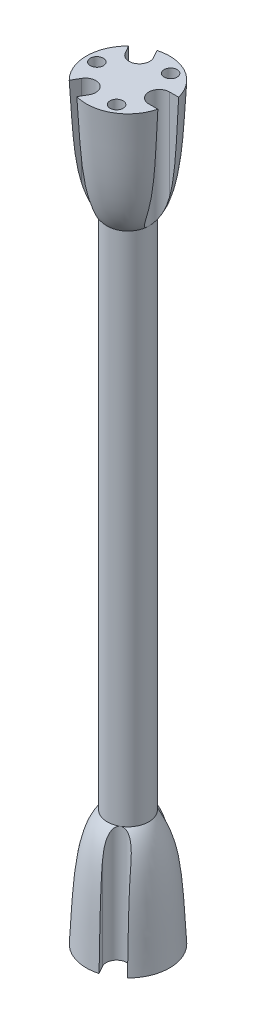
SolidWorks part; units mm, degrees
ref_plane "Front Plane" through (0, 0, 0) normal (0, 0, 1) x (1, 0, 0)
ref_plane "Top Plane" through (0, 0, 0) normal (0, 1, 0) x (1, 0, 0)
ref_plane "Right Plane" through (0, 0, 0) normal (1, 0, 0) x (0, 0, -1)
sketch "Sketch1" plane through (0, 0, 0) normal (0, 0, 1) x (1, 0, 0)
  line L0 (0, 0) -> (0, 38.1)
  line L1 (0, 0) -> (12.7, 0)
  line L9 (0, 228.6) -> (12.7, 228.6)
  line L10 (0, 228.6) -> (0, 190.5)
  spline S0 degree 3 poles (0, 38.1) (12.0762, 38.4029) (11.5808, 18.1012) (12.7, 0) knots 0 0 0 0 1 1 1 1
  spline S1 degree 3 poles (0, 190.5) (12.0762, 190.1971) (11.5808, 210.4988) (12.7, 228.6) knots 0 0 0 0 1 1 1 1
  point P8 (-152.1908, 114.3)
  dimension "D1" = 12.7
  dimension "D2" = 38.1
revolve "Revolve1" add sketch "Sketch1" angle 360 about L0
sketch "Sketch2" plane through (0, 0, 0) normal (0, -1, 0) x (1, 0, 0)
  circle A0 centre (0, 0) radius 6.35
  dimension "D1" = 12.7
extrude "Boss-Extrude1" add sketch "Sketch2" against normal blind 228.6
sketch "Sketch3" plane through (0, 0, 0) normal (0, -1, 0) x (-1, 0, 0)
  circle A0 centre (-9.525, 0) radius 2
  circle A1 centre (4.7625, 8.2489) radius 2
  circle A2 centre (4.7625, -8.2489) radius 2
  point P9 (0, 0)
  dimension "D1" = 4
  dimension "D2" = 9.525
  dimension "D3" = 3
extrude "Cut-Extrude1" cut sketch "Sketch3" against normal blind 7
sketch "Sketch4" plane through (0, 0, 0) normal (0, -1, 0) x (1, 0, 0)
  line L0 (7.9375, 13.7482) -> (4.7625, 8.2489) construction
  line L1 (-15.875, 0) -> (-9.525, 0) construction
  line L2 (-15.875, 3.175) -> (-9.525, 3.175)
  line L3 (-15.875, -3.175) -> (-9.525, -3.175)
  line L4 (10.6871, 12.1607) -> (7.5121, 6.6614)
  line L5 (5.1879, 15.3357) -> (2.0129, 9.8364)
  line L6 (7.9375, -13.7482) -> (4.7625, -8.2489) construction
  line L7 (5.1879, -15.3357) -> (2.0129, -9.8364)
  line L8 (10.6871, -12.1607) -> (7.5121, -6.6614)
  circle A1 centre (0, 0) radius 12.7 construction
  arc A2 (-15.875, 3.175) -> (-15.875, -3.175) centre (-15.875, 0) ccw
  arc A3 (-9.525, -3.175) -> (-9.525, 3.175) centre (-9.525, 0) ccw
  arc A4 (10.6871, 12.1607) -> (5.1879, 15.3357) centre (7.9375, 13.7482) ccw
  arc A5 (2.0129, 9.8364) -> (7.5121, 6.6614) centre (4.7625, 8.2489) ccw
  arc A6 (5.1879, -15.3357) -> (10.6871, -12.1607) centre (7.9375, -13.7482) ccw
  arc A7 (7.5121, -6.6614) -> (2.0129, -9.8364) centre (4.7625, -8.2489) ccw
  point P2 (0, 0)
  point P3 (0, 0)
  point P6 (-12.7, 0)
  point P14 (6.35, 10.9985)
  point P21 (6.35, -10.9985)
  point P26 (0, 0)
  point P27 (0, 0)
  point P28 (0, 0)
  point P29 (-9.525, -3.0626)
  dimension "D1" = 3
  dimension "D3" = 3.175
  dimension "D2" = 9.525
extrude "Cut-Extrude3" cut sketch "Sketch4" against normal up to next
sketch "Sketch5" plane through (0, 228.6, 0) normal (0, 1, 0) x (1, 0, 0)
  circle A0 centre (-9.525, 0) radius 2
  circle A1 centre (4.7625, 8.2489) radius 2
  circle A2 centre (4.7625, -8.2489) radius 2
  point P9 (0, 0)
  dimension "D1" = 4
  dimension "D2" = 9.525
  dimension "D3" = 3
extrude "Cut-Extrude4" cut sketch "Sketch5" against normal blind 7
sketch "Sketch6" plane through (0, 228.6, 0) normal (0, 1, 0) x (1, 0, 0)
  line L0 (15.875, 0) -> (9.525, 0) construction
  line L3 (15.875, -3.175) -> (9.525, -3.175)
  line L4 (15.875, 3.175) -> (9.525, 3.175)
  line L5 (-7.9375, -13.7482) -> (-4.7625, -8.2489) construction
  line L6 (-10.6871, -12.1607) -> (-7.5121, -6.6614)
  line L7 (-5.1879, -15.3357) -> (-2.0129, -9.8364)
  line L8 (-7.9375, 13.7482) -> (-4.7625, 8.2489) construction
  line L9 (-5.1879, 15.3357) -> (-2.0129, 9.8364)
  line L10 (-10.6871, 12.1607) -> (-7.5121, 6.6614)
  circle A4 centre (0, 0) radius 12.7 construction
  arc A5 (15.875, -3.175) -> (15.875, 3.175) centre (15.875, 0) ccw
  arc A6 (9.525, 3.175) -> (9.525, -3.175) centre (9.525, 0) ccw
  arc A7 (-10.6871, -12.1607) -> (-5.1879, -15.3357) centre (-7.9375, -13.7482) ccw
  arc A8 (-2.0129, -9.8364) -> (-7.5121, -6.6614) centre (-4.7625, -8.2489) ccw
  arc A9 (-5.1879, 15.3357) -> (-10.6871, 12.1607) centre (-7.9375, 13.7482) ccw
  arc A10 (-7.5121, 6.6614) -> (-2.0129, 9.8364) centre (-4.7625, 8.2489) ccw
  point P4 (12.7, 0)
  point P14 (-6.35, -10.9985)
  point P21 (-6.35, 10.9985)
  point P26 (0, 0)
  dimension "D1" = 3
  dimension "D3" = 3.175
extrude "Cut-Extrude5" cut sketch "Sketch6" against normal up to next and the other way through all
